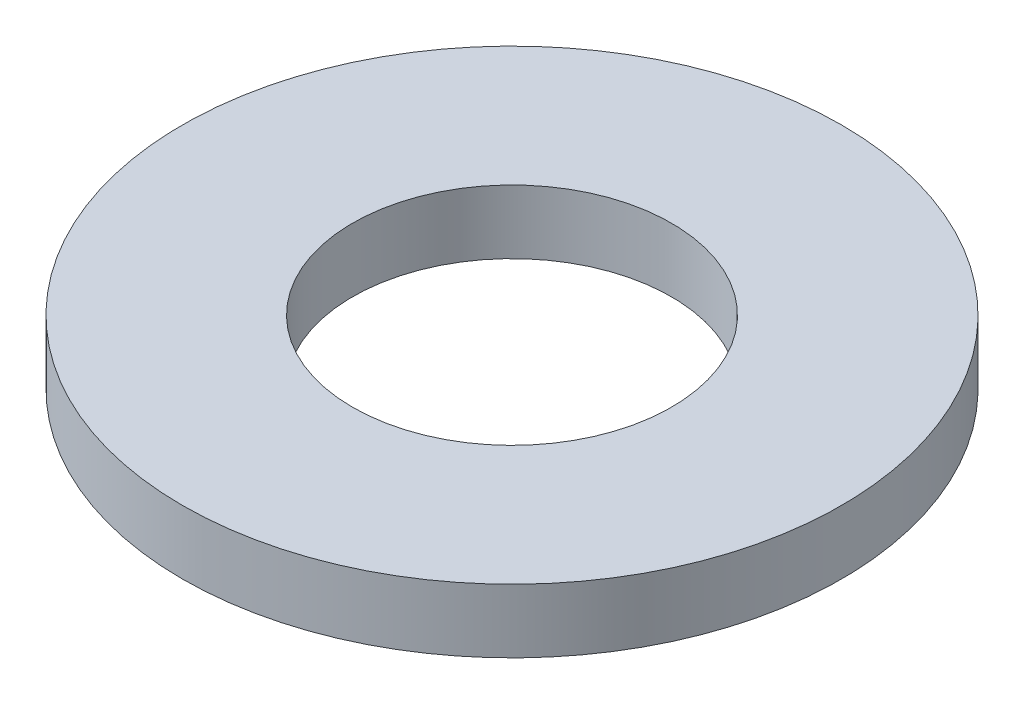
SolidWorks part; units mm, degrees
ref_plane "Front Plane" through (0, 0, 0) normal (0, 0, 1) x (1, 0, 0)
ref_plane "Top Plane" through (0, 0, 0) normal (0, 1, 0) x (1, 0, 0)
ref_plane "Right Plane" through (0, 0, 0) normal (1, 0, 0) x (0, 0, -1)
sketch "Sketch1" plane through (0, 0, 0) normal (0, 1, 0) x (1, 0, 0)
  circle A0 centre (0, 0) radius 31
  circle A1 centre (0, 0) radius 15
  dimension "D1" = 62
  dimension "D2" = 30
extrude "Boss-Extrude1" add sketch "Sketch1" along normal mid plane 6
